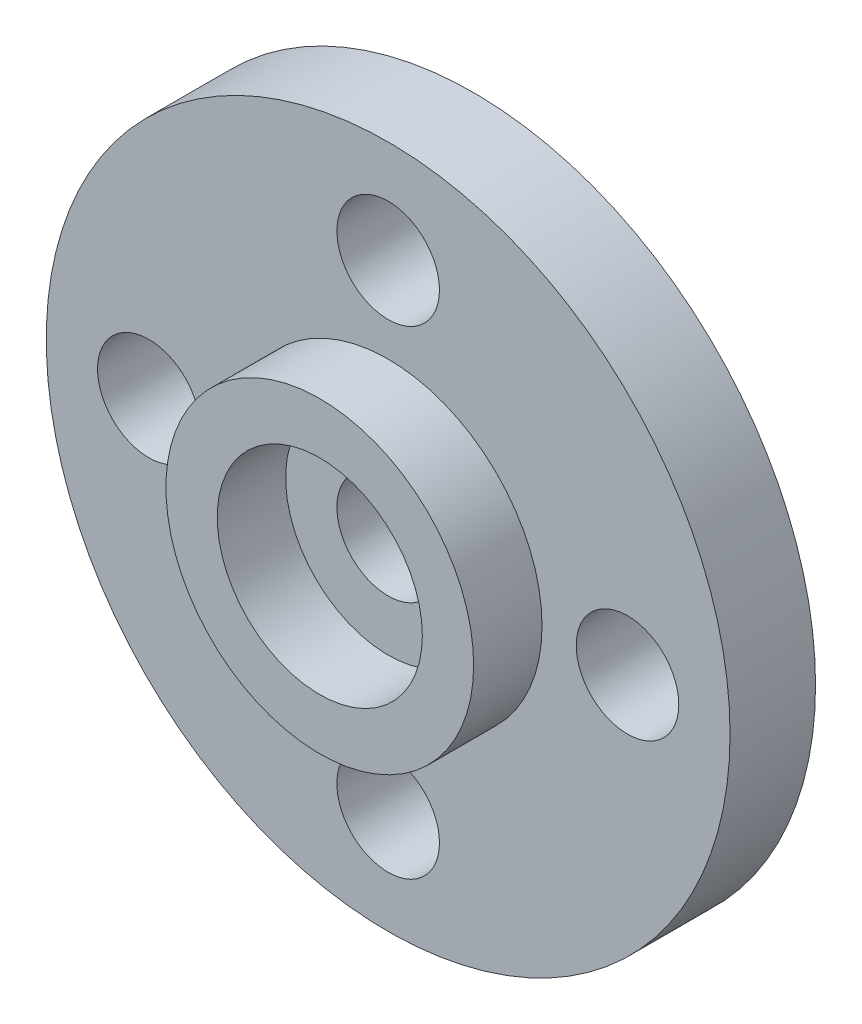
SolidWorks part; units mm, degrees
ref_plane "前视基准面" through (0, 0, 0) normal (0, 0, 1) x (1, 0, 0)
ref_plane "上视基准面" through (0, 0, 0) normal (0, 1, 0) x (1, 0, 0)
ref_plane "右视基准面" through (0, 0, 0) normal (1, 0, 0) x (0, 0, -1)
sketch "草图1" plane through (0, 0, 0) normal (0, 0, 1) x (1, 0, 0)
  circle A0 centre (0, 0) radius 10
  circle A1 centre (0, 0) radius 7
  circle A2 centre (0, 0) radius 1.5
  circle A3 centre (0, 7) radius 1.5
  circle A4 centre (-7, 0) radius 1.5
  circle A5 centre (7, 0) radius 1.5
  circle A6 centre (0, -7) radius 1.5
  dimension "D1" = 20
  dimension "D2" = 14
  dimension "D3" = 3
  dimension "D4" = 3
  dimension "D5" = 3
  dimension "D6" = 3
  dimension "D7" = 3
extrude "凸台-拉伸1" add sketch "草图1" along normal blind 2.5 contours A0 A6 A1 A4 A3 A5 | A6 A1 A5 A3 A4 A2
sketch "草图2" plane through (0, 0, 2.5) normal (0, 0, 1) x (1, 0, 0)
  circle A0 centre (0, 0) radius 3
  circle A1 centre (0, 0) radius 4.5
  dimension "D1" = 9
  dimension "D2" = 6
extrude "凸台-拉伸2" add sketch "草图2" along normal blind 2
